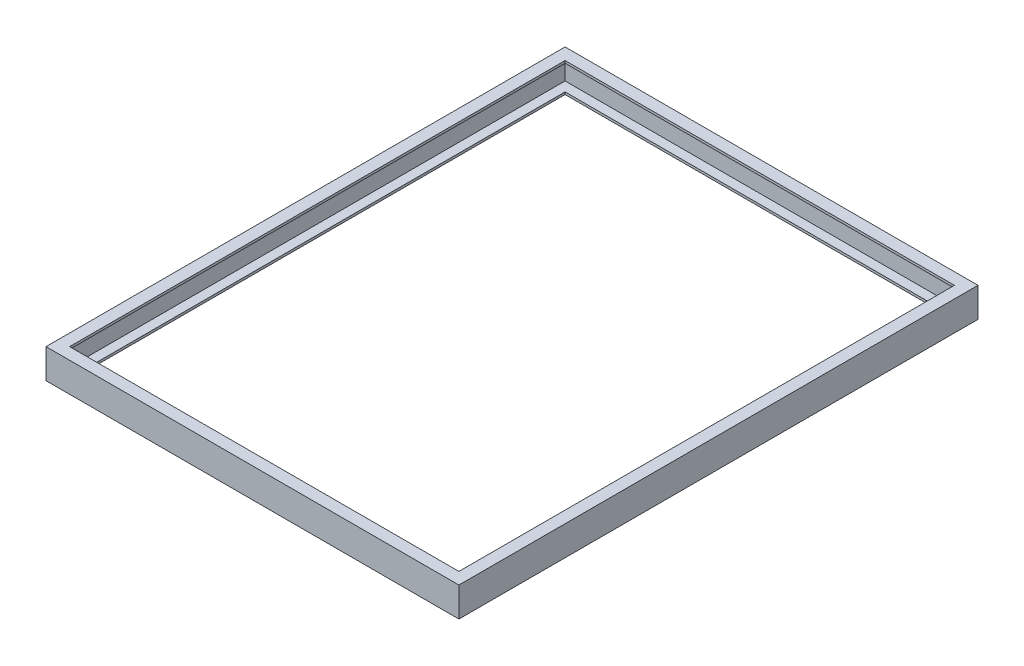
SolidWorks part; units mm, degrees
ref_plane "Front Plane" through (0, 0, 0) normal (0, 0, 1) x (1, 0, 0)
ref_plane "Top Plane" through (0, 0, 0) normal (0, 1, 0) x (1, 0, 0)
ref_plane "Right Plane" through (0, 0, 0) normal (1, 0, 0) x (0, 0, -1)
sketch "Sketch1" plane through (0, 0, 0) normal (0, 1, 0) x (1, 0, 0)
  line L0 (-10, 10) -> (-10, 430)
  line L1 (0, 0) -> (-350, 0)
  line L2 (0, 0) -> (0, 440)
  line L3 (0, 440) -> (-350, 440)
  line L4 (-350, 0) -> (-350, 440)
  line L5 (-10, 430) -> (-340, 430)
  line L6 (-340, 10) -> (-340, 430)
  line L7 (-10, 10) -> (-340, 10)
  dimension "D1" = 350
  dimension "D2" = 440
  dimension "D3" = 10
extrude "Boss-Extrude1" add sketch "Sketch1" along normal blind 25
shell "Shell1" thickness 2
